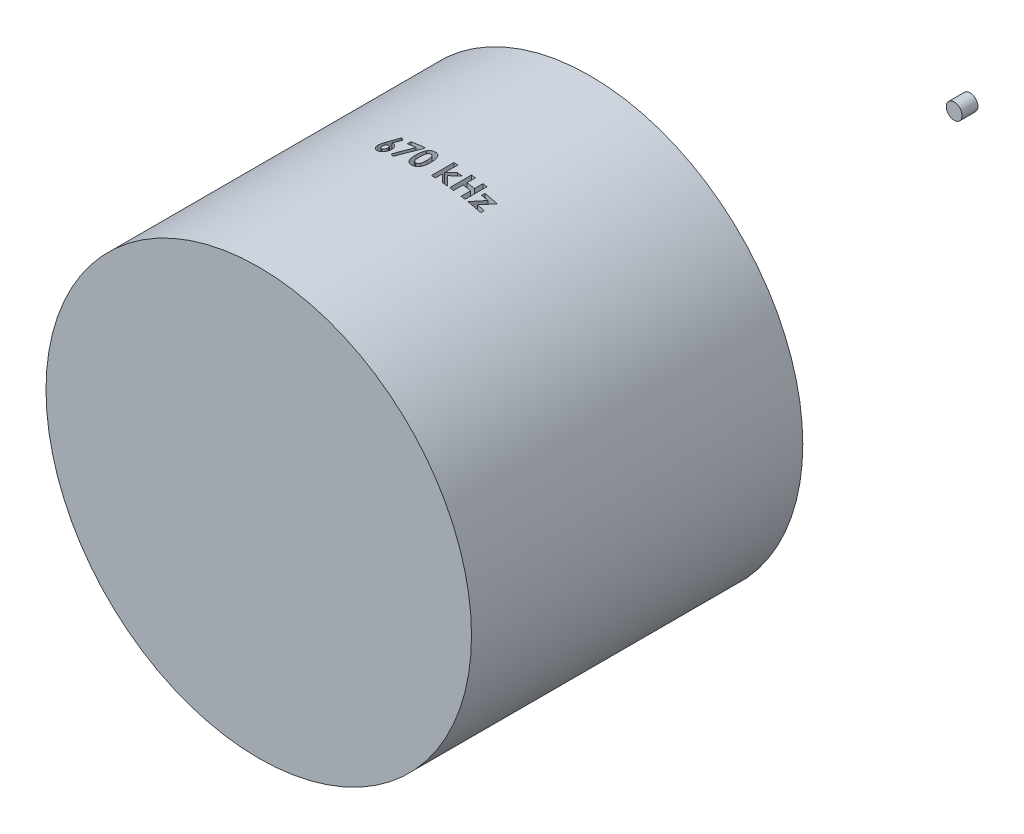
SolidWorks part; units mm, degrees
ref_plane "Front Plane" through (0, 0, 0) normal (0, 0, 1) x (1, 0, 0)
ref_plane "Top Plane" through (0, 0, 0) normal (0, 1, 0) x (1, 0, 0)
ref_plane "Right Plane" through (0, 0, 0) normal (1, 0, 0) x (0, 0, -1)
sketch "Sketch2" plane through (0, 0, 0) normal (1, 0, 0) x (0, 0, -1)
  line L0 (0, 0) -> (82.3751, 0) construction
  line L1 (0, 0) -> (0, 34.036)
  line L2 (0, 34.036) -> (53, 34.036)
  line L3 (53, 34.036) -> (53, 0)
  line L4 (53, 0) -> (0, 0)
  line L5 (111.256, 0) -> (111.256, 1.27)
  line L6 (111.256, 1.27) -> (113.796, 1.27)
  line L7 (113.796, 1.27) -> (113.796, 0)
  line L8 (111.256, 0) -> (113.796, 0)
  point P8 (112.526, 0)
  dimension "D1" = 34.036
  dimension "D2" = 53
  dimension "D3" = 59.526
  dimension "D4" = 2.54
  dimension "D5" = 1.27
revolve "Revolve1" add sketch "Sketch2" angle 360 about L0
sketch "Sketch3" plane through (0, 0, 0) normal (0, 1, 0) x (1, 0, 0)
  line L0 (-34.036, 26.5) -> (34.036, 26.5) construction
  line L1 (-34.036, 53) -> (-34.036, 0) construction
  line L2 (34.036, 0) -> (34.036, 53) construction
  text T0 "<b>670 kHz</b>"
extrude "Cut-Extrude1" cut sketch "Sketch3" against normal blind 22.86 from offset 50.8
